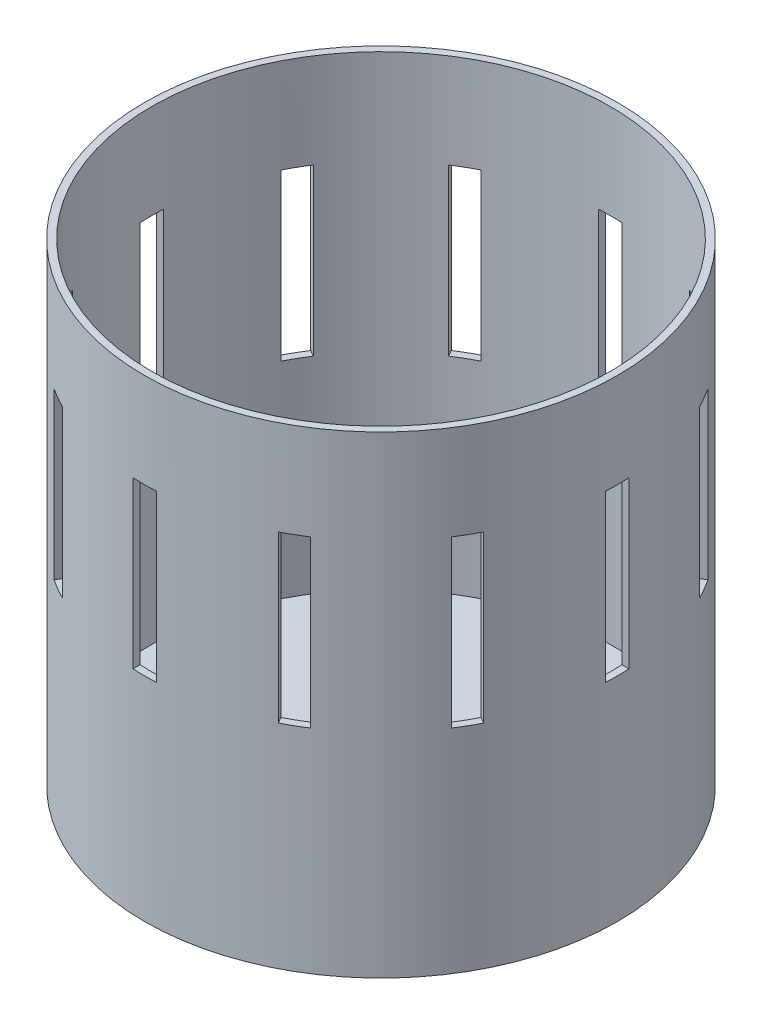
SolidWorks part; units mm, degrees
ref_plane "Alzado" through (0, 0, 0) normal (0, 0, 1) x (1, 0, 0)
ref_plane "Planta" through (0, 0, 0) normal (0, 1, 0) x (1, 0, 0)
ref_plane "Vista lateral" through (0, 0, 0) normal (1, 0, 0) x (0, 0, -1)
sketch "Croquis2" plane through (0, 0, 0) normal (0, 0, 1) x (1, 0, 0)
  line L0 (0, 0) -> (-10, 0)
  line L1 (-10, 0) -> (-10, 5)
  line L2 (-10, 5) -> (-50, 5)
  line L3 (-50, 5) -> (-50, 105)
  line L4 (-50, 105) -> (0, 105)
  line L5 (0, 0) -> (0, 105)
  line L7 (0, 0) -> (0, 105) construction
  dimension "D1" = 50
  dimension "D2" = 10
  dimension "D3" = 100
  dimension "D4" = 5
revolve "Revolución2" add sketch "Croquis2" angle 360 about L7
sketch "Croquis3" plane through (0, 105, 0) normal (0, 1, 0) x (1, 0, 0)
  circle A0 centre (0, 0) radius 48.5
  dimension "D1" = 97
extrude "Cortar-Extruir1" cut sketch "Croquis3" against normal blind 98.5
sketch "Croquis4" plane through (0, 0, 0) normal (0, -1, 0) x (1, 0, 0)
  circle A0 centre (0, 0) radius 1
  dimension "D1" = 2
extrude "Cortar-Extruir2" cut sketch "Croquis4" against normal blind 98.5
sketch "Croquis6" plane through (0, 0, 0) normal (0, 0, 1) x (1, 0, 0)
  line L0 (0, 0) -> (0, 85) construction
  line L1 (-2.5, 85) -> (2.5, 85)
  line L2 (-2.5, 85) -> (-2.5, 50)
  line L3 (-2.5, 50) -> (2.5, 50)
  line L4 (2.5, 85) -> (2.5, 50)
  dimension "D1" = 5
  dimension "D2" = 35
  dimension "D3" = 85
extrude "Cortar-Extruir3" cut sketch "Croquis6" against normal blind 98.5
pattern_circular "MatrizC1" count 12 over 360 about axis through (0, 0, 0) along (0, 1, 0) of "Cortar-Extruir3"
